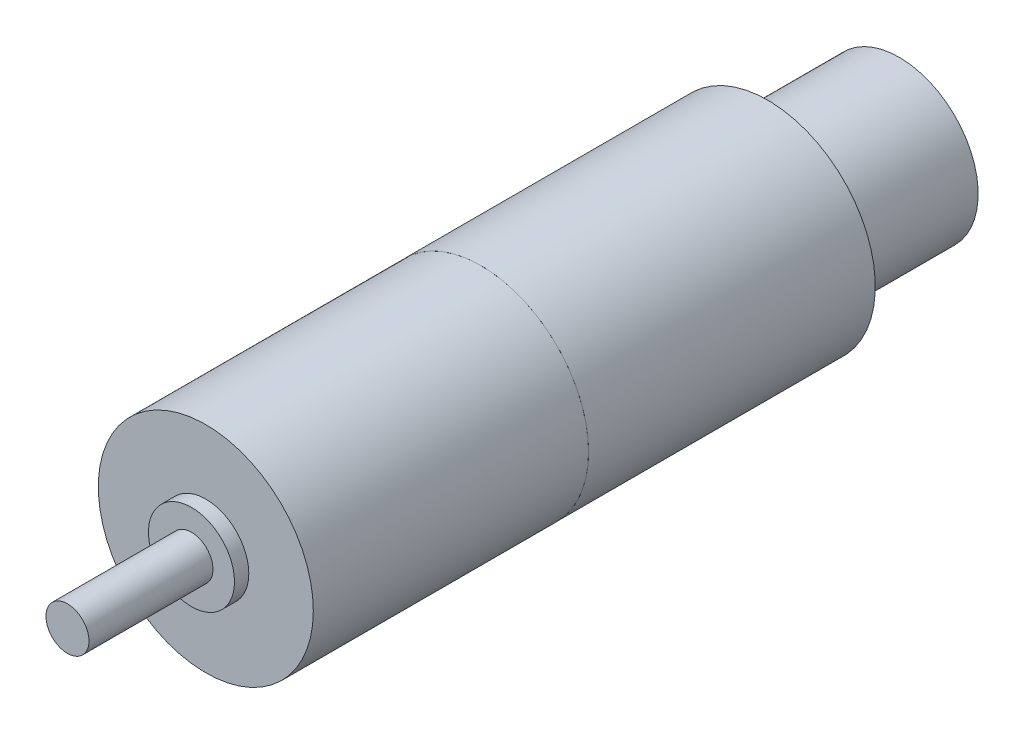
SolidWorks part; units mm, degrees
ref_plane "Front Plane" through (0, 0, 0) normal (0, 0, 1) x (1, 0, 0)
ref_plane "Top Plane" through (0, 0, 0) normal (0, 1, 0) x (1, 0, 0)
ref_plane "Right Plane" through (0, 0, 0) normal (1, 0, 0) x (0, 0, -1)
sketch "Sketch1" plane through (0, 0, 0) normal (0, 0, 1) x (1, 0, 0)
  circle A0 centre (0, 0) radius 15
  dimension "D1" = 30
extrude "Boss-Extrude1" add sketch "Sketch1" along normal blind 38.4 contours A0
sketch "Sketch2" plane through (0, 0, 0) normal (0, 0, -1) x (-1, 0, 0)
  circle A0 centre (0, 0) radius 15
extrude "Boss-Extrude2" add sketch "Sketch2" along normal blind 40 separate body
sketch "Sketch3" plane through (0, 0, 38.4) normal (0, 0, 1) x (1, 0, 0)
  circle A0 centre (0, 0) radius 6
extrude "Boss-Extrude3" add sketch "Sketch3" along normal blind 2 contours A0
sketch "Sketch4" plane through (0, 0, -40) normal (0, 0, -1) x (-1, 0, 0)
  circle A0 centre (0, 0) radius 11
extrude "Boss-Extrude4" add sketch "Sketch4" along normal blind 18.35 separate body contours A0
sketch "Sketch5" plane through (0, 0, 40.4) normal (0, 0, 1) x (1, 0, 0)
  circle A0 centre (0, 0) radius 3
extrude "Boss-Extrude5" add sketch "Sketch5" along normal blind 17.3 separate body contours A0
